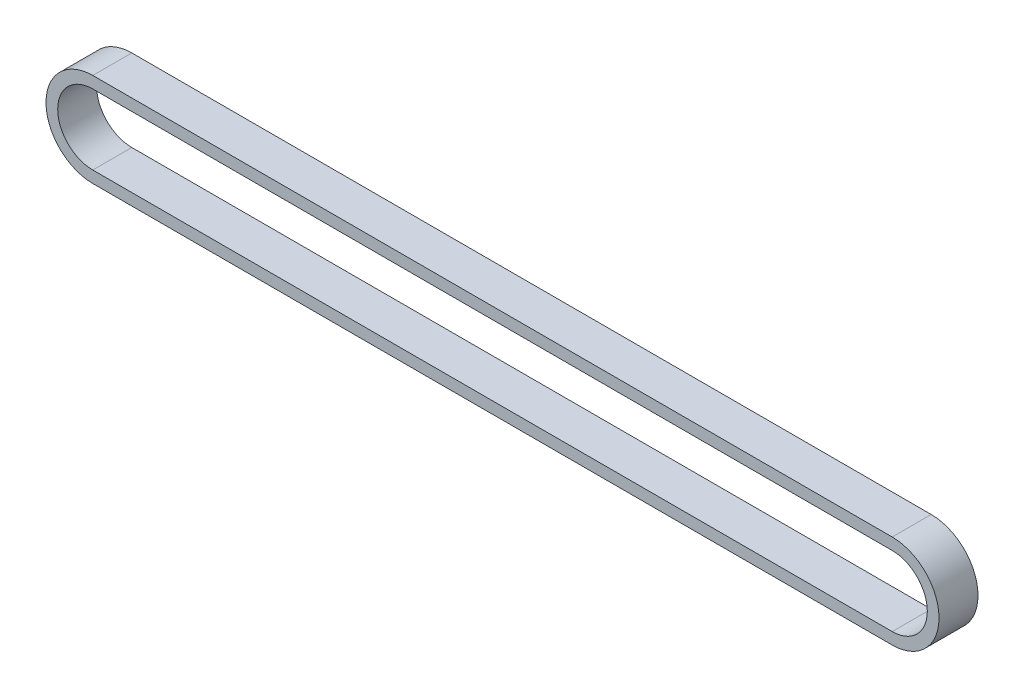
SolidWorks part; units mm, degrees
ref_plane "前视基准面" through (0, 0, 0) normal (0, 0, 1) x (1, 0, 0)
ref_plane "上视基准面" through (0, 0, 0) normal (0, 1, 0) x (1, 0, 0)
ref_plane "右视基准面" through (0, 0, 0) normal (1, 0, 0) x (0, 0, -1)
other "Configuration Table"
sketch "草图1" plane through (0, 0, 0) normal (0, 0, 1) x (1, 0, 0)
  line L0 (0, 0) -> (205, 0) construction
  line L1 (0, 9) -> (205, 9)
  line L2 (0, -9) -> (205, -9)
  line L3 (0, 12) -> (205, 12)
  line L4 (0, -12) -> (205, -12)
  arc A0 (0, 9) -> (0, -9) centre (0, 0) ccw
  arc A1 (205, -9) -> (205, 9) centre (205, 0) ccw
  arc A2 (205, -12) -> (205, 12) centre (205, 0) ccw
  arc A3 (0, 12) -> (0, -12) centre (0, 0) ccw
  point P3 (102.5, 0)
  point P8 (-9, 0)
  point P9 (214, 0)
  dimension "D2" = 9
  dimension "D1" = 205
  dimension "D3" = 3
extrude "凸台-拉伸1" add sketch "草图1" along normal blind 10
